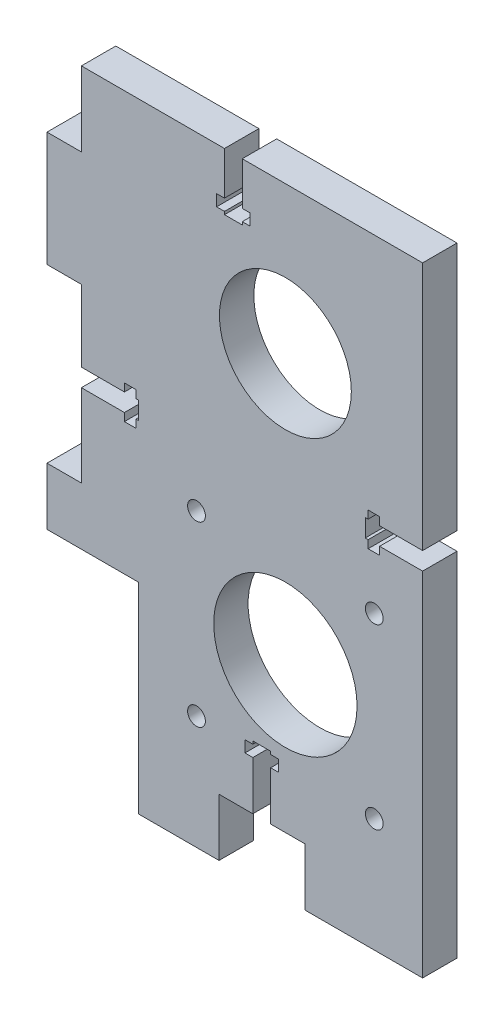
SolidWorks part; units mm, degrees
ref_plane "Płaszczyzna przednia" through (0, 0, 0) normal (0, 0, 1) x (1, 0, 0)
ref_plane "Płaszczyzna górna" through (0, 0, 0) normal (0, 1, 0) x (1, 0, 0)
ref_plane "Płaszczyzna prawa" through (0, 0, 0) normal (1, 0, 0) x (0, 0, -1)
sketch "Szkic1" plane through (0, 0, 0) normal (0, 0, 1) x (1, 0, 0)
  line L0 (56.4927, -30.833) -> (-9.0073, -30.833)
  line L1 (56.4927, -30.833) -> (56.4927, 83.167)
  line L2 (-9.0073, -30.833) -> (-9.0073, 83.167)
  line L3 (56.4927, 83.167) -> (-9.0073, 83.167)
  dimension "D1" = 65.5
  dimension "D2" = 114
extrude "Dodanie-wyciągnięcie1" add sketch "Szkic1" along normal blind 6
sketch "Szkic2" plane through (0, 0, 6) normal (0, 0, 1) x (1, 0, 0)
  circle A0 centre (32.5627, 4.5049) radius 12.5
  circle A2 centre (32.5627, 4.5049) radius 2.25 construction
  dimension "D1" = 25
  dimension "D2" = 0
extrude "Wytnij-wyciągnięcie2" cut sketch "Szkic2" against normal blind 6
sketch "Szkic3" plane through (0, 0, 0) normal (0, 0, -1) x (-1, 0, 0)
  circle A0 centre (-48.0627, -10.9951) radius 1.5 construction
  circle A1 centre (-17.0627, -10.9951) radius 1.5 construction
  circle A2 centre (-17.0627, 20.0049) radius 1.5 construction
  circle A3 centre (-48.0627, 20.0049) radius 1.5 construction
  circle A4 centre (-48.0627, -10.9951) radius 1.5
  circle A5 centre (-17.0627, -10.9951) radius 1.5
  circle A6 centre (-17.0627, 20.0049) radius 1.5
  circle A7 centre (-48.0627, 20.0049) radius 1.5
  circle A8 centre (-17.0627, 20.0049) radius 1.55
  circle A9 centre (-17.0627, -10.9951) radius 1.55
  circle A10 centre (-48.0627, -10.9951) radius 1.55
  circle A11 centre (-48.0627, 20.0049) radius 1.55
  dimension "D1" = 3.1
  dimension "D2" = 3.1
  dimension "D3" = 3.1
  dimension "D4" = 3.1
sketch "Szkic4" plane through (0, 0, 0) normal (0, 0, -1) x (-1, 0, 0)
  circle A0 centre (-17.0627, -10.9951) radius 1.55 construction
  circle A1 centre (-17.0627, 20.0049) radius 1.55 construction
  circle A2 centre (-48.0627, 20.0049) radius 1.55 construction
  circle A3 centre (-48.0627, -10.9951) radius 1.55 construction
  circle A4 centre (-17.0627, -10.9951) radius 1.55
  circle A5 centre (-17.0627, 20.0049) radius 1.55
  circle A6 centre (-48.0627, 20.0049) radius 1.55
  circle A7 centre (-48.0627, -10.9951) radius 1.55
extrude "Wytnij-wyciągnięcie3" cut sketch "Szkic4" against normal blind 6
sketch "Szkic5" plane through (0, 0, 6) normal (0, 0, 1) x (1, 0, 0)
  line L0 (-9.0073, 83.167) -> (-9.0073, -30.833) construction
  line L1 (-9.0073, 4.167) -> (-9.0073, -30.833)
  line L2 (-9.0073, -30.833) -> (56.4927, -30.833) construction
  line L3 (-9.0073, 4.167) -> (-3.0073, 4.167)
  line L4 (20.9927, -20.833) -> (35.9927, -20.833)
  line L5 (56.4927, 77.167) -> (56.4927, 83.167)
  line L6 (-9.0073, 83.167) -> (-9.0073, 64.167)
  line L7 (-9.0073, 64.167) -> (-3.0073, 64.167)
  line L8 (-3.0073, 77.167) -> (-3.0073, 64.167)
  line L9 (-9.0073, 44.167) -> (-3.0073, 44.167)
  line L10 (-9.0073, 44.167) -> (-9.0073, 14.167)
  line L11 (-9.0073, 14.167) -> (-3.0073, 14.167)
  line L12 (-3.0073, 44.167) -> (-3.0073, 14.167)
  line L13 (-3.0073, 4.167) -> (6.9927, 4.167)
  line L14 (-9.0073, -30.833) -> (6.9927, -30.833)
  line L15 (20.9927, -20.833) -> (20.9927, -30.833)
  line L16 (20.9927, -30.833) -> (35.9927, -30.833)
  line L17 (6.9927, 4.167) -> (6.9927, -30.833)
  line L22 (35.9927, -20.833) -> (35.9927, -30.833)
  line L25 (56.4927, 77.167) -> (-3.0073, 77.167)
  line L27 (56.4927, 83.167) -> (-9.0073, 83.167)
  dimension "D8" = 16
  dimension "D1" = 6
  dimension "D2" = 35
  dimension "D3" = 6
  dimension "D4" = 30
  dimension "D5" = 20
  dimension "D6" = 10
  dimension "D7" = 6
  dimension "D9" = 6
  dimension "D11" = 15
  dimension "D13" = 10
extrude "Wytnij-wyciągnięcie4" cut sketch "Szkic5" against normal blind 6
sketch "Szkic6" plane through (0, 0, 6) normal (0, 0, 1) x (1, 0, 0)
  line L5 (-3.0073, 14.167) -> (-3.0073, 44.167) construction
  line L10 (-3.0073, 31.667) -> (4.4927, 31.667)
  line L11 (-3.0073, 31.667) -> (-3.0073, 28.567)
  line L12 (-3.0073, 28.567) -> (4.4927, 28.567)
  line L13 (6.9927, 31.667) -> (6.9927, 28.567)
  line L14 (6.4927, 28.567) -> (6.4927, 27.192)
  line L15 (4.4927, 33.042) -> (6.4927, 33.042)
  line L16 (4.4927, 33.042) -> (4.4927, 31.667)
  line L17 (4.4927, 27.192) -> (6.4927, 27.192)
  line L18 (6.4927, 33.042) -> (6.4927, 31.667)
  line L19 (6.4927, 31.667) -> (6.9927, 31.667)
  line L20 (4.4927, 28.567) -> (4.4927, 27.192)
  line L21 (6.4927, 28.567) -> (6.9927, 28.567)
  line L27 (-3.0073, 44.167) -> (-9.0073, 44.167) construction
  line L29 (26.8927, -20.833) -> (29.9927, -20.833)
  line L30 (26.8927, -20.833) -> (26.8927, -12.333)
  line L31 (26.8927, -9.833) -> (29.9927, -9.833)
  line L32 (29.9927, -20.833) -> (29.9927, -12.333)
  line L33 (29.9927, -10.333) -> (31.3677, -10.333)
  line L34 (25.5177, -10.333) -> (26.8927, -10.333)
  line L35 (25.5177, -10.333) -> (25.5177, -12.333)
  line L36 (25.5177, -12.333) -> (26.8927, -12.333)
  line L37 (31.3677, -10.333) -> (31.3677, -12.333)
  line L38 (26.8927, -10.333) -> (26.8927, -9.833)
  line L39 (29.9927, -12.333) -> (31.3677, -12.333)
  line L40 (29.9927, -10.333) -> (29.9927, -9.833)
  line L42 (35.9927, -20.833) -> (20.9927, -20.833) construction
  dimension "D7" = 0
  dimension "D8" = 5.85
  dimension "D9" = 1.375
  dimension "D10" = 10
  dimension "D11" = 0.5
  dimension "D12" = 2
  dimension "D13" = 3.1
  dimension "D14" = 12.5
  dimension "D15" = 11
  dimension "D16" = 0.5
  dimension "D17" = 1.375
  dimension "D18" = 5.85
  dimension "D19" = 3.1
  dimension "D20" = 2
extrude "Wytnij-wyciągnięcie5" cut sketch "Szkic6" against normal blind 6
sketch "Szkic7" plane through (0, 0, 6) normal (0, 0, 1) x (1, 0, 0)
  line L1 (56.4927, 33.717) -> (48.9927, 33.717)
  line L2 (56.4927, 33.717) -> (56.4927, 30.617)
  line L3 (56.4927, 30.617) -> (48.9927, 30.617)
  line L4 (46.4927, 33.717) -> (46.4927, 30.617)
  line L5 (46.9927, 33.717) -> (46.4927, 33.717)
  line L6 (46.9927, 35.092) -> (48.9927, 35.092)
  line L7 (46.9927, 35.092) -> (46.9927, 33.717)
  line L8 (46.9927, 29.242) -> (48.9927, 29.242)
  line L9 (48.9927, 35.092) -> (48.9927, 33.717)
  line L10 (46.9927, 30.617) -> (46.9927, 29.242)
  line L11 (46.9927, 30.617) -> (46.4927, 30.617)
  line L12 (48.9927, 30.617) -> (48.9927, 29.242)
  line L13 (-3.0073, 77.167) -> (56.4927, 77.167) construction
  line L14 (56.4927, -30.833) -> (56.4927, 77.167) construction
  line L15 (21.9427, 69.667) -> (20.5677, 69.667)
  line L16 (21.9427, 77.167) -> (25.0427, 77.167)
  line L17 (21.9427, 77.167) -> (21.9427, 69.667)
  line L18 (21.9427, 67.167) -> (25.0427, 67.167)
  line L19 (25.0427, 77.167) -> (25.0427, 69.667)
  line L20 (26.4177, 69.667) -> (25.0427, 69.667)
  line L21 (26.4177, 69.667) -> (26.4177, 67.667)
  line L22 (26.4177, 67.667) -> (25.0427, 67.667)
  line L23 (20.5677, 69.667) -> (20.5677, 67.667)
  line L24 (21.9427, 67.667) -> (21.9427, 67.167)
  line L25 (21.9427, 67.667) -> (20.5677, 67.667)
  line L26 (25.0427, 67.667) -> (25.0427, 67.167)
  line L28 (-3.0073, 64.167) -> (-3.0073, 77.167) construction
  point P14 (56.4927, 32.167)
  point P29 (23.4927, 77.167)
  dimension "D1" = 10
  dimension "D2" = 5.85
  dimension "D3" = 3.1
  dimension "D4" = 0.5
  dimension "D5" = 1.375
  dimension "D6" = 45
  dimension "D7" = 10
  dimension "D8" = 2
  dimension "D9" = 5.85
  dimension "D10" = 1.375
  dimension "D11" = 3.1
  dimension "D12" = 0.5
  dimension "D13" = 0
  dimension "D14" = 26.5
  dimension "D15" = 2
extrude "Wytnij-wyciągnięcie6" cut sketch "Szkic7" against normal blind 6
sketch "Szkic8" plane through (0, 0, 6) normal (0, 0, 1) x (1, 0, 0)
  circle A0 centre (32.5627, 51.5049) radius 11.5
  circle A1 centre (32.5627, 4.5049) radius 12.5 construction
  dimension "D1" = 23
  dimension "D3" = 0
  dimension "D2" = 47
extrude "Wytnij-wyciągnięcie7" cut sketch "Szkic8" against normal blind 10
equation "\"tolerancja_wpusy\"=0.2"
equation "\"dlugosc_wpustu_duzy\"=20"
equation "\"srednica_otworu_M3\"=3.1"
equation "\"szerokosc_nogi_T\"=3.1"
equation "\"dlugosc_T_30\"=11"
equation "\"grubosc_na_nakretke_kwadrat\"=2"
equation "\"szerokosc_na_nakretke_kwadrat\"=5.85"
equation "\"wyokosc_nadstawki_T\"=0.5"
equation "\"dlugosc_T_20_6\"=14"
equation "\"D1@Szkic3\"=\"srednica_otworu_M3\""
equation "\"D2@Szkic3\"=\"srednica_otworu_M3\""
equation "\"D3@Szkic3\"=\"srednica_otworu_M3\""
equation "\"D4@Szkic3\"=\"srednica_otworu_M3\""
equation "\"D8@Szkic6\" = \"szerokosc_na_nakretke_kwadrat\""
equation "\"D9@Szkic6\"=(\"szerokosc_na_nakretke_kwadrat\"-\"szerokosc_nogi_T\")/2"
equation "\"D11@Szkic6\"=\"wyokosc_nadstawki_T\""
equation "\"D12@Szkic6\"=\"grubosc_na_nakretke_kwadrat\""
equation "\"D13@Szkic6\"=\"szerokosc_nogi_T\""
equation "\"D16@Szkic6\"=\"wyokosc_nadstawki_T\""
equation "\"D17@Szkic6\"=(\"szerokosc_na_nakretke_kwadrat\"-\"szerokosc_nogi_T\")/2"
equation "\"D18@Szkic6\"=\"szerokosc_na_nakretke_kwadrat\""
equation "\"D19@Szkic6\"=\"szerokosc_nogi_T\""
equation "\"D20@Szkic6\"=\"grubosc_na_nakretke_kwadrat\""
equation "\"D2@Szkic7\"=\"szerokosc_na_nakretke_kwadrat\""
equation "\"D3@Szkic7\"=\"szerokosc_nogi_T\""
equation "\"D4@Szkic7\"=\"wyokosc_nadstawki_T\""
equation "\"D5@Szkic7\"=(\"szerokosc_na_nakretke_kwadrat\"-\"szerokosc_nogi_T\")/2"
equation "\"D8@Szkic7\"=\"grubosc_na_nakretke_kwadrat\""
equation "\"D9@Szkic7\"=\"szerokosc_na_nakretke_kwadrat\""
equation "\"D10@Szkic7\"=(\"szerokosc_na_nakretke_kwadrat\"-\"szerokosc_nogi_T\")/2"
equation "\"D11@Szkic7\"=\"szerokosc_nogi_T\""
equation "\"D12@Szkic7\"=\"wyokosc_nadstawki_T\""
equation "\"D15@Szkic7\"=\"grubosc_na_nakretke_kwadrat\""
